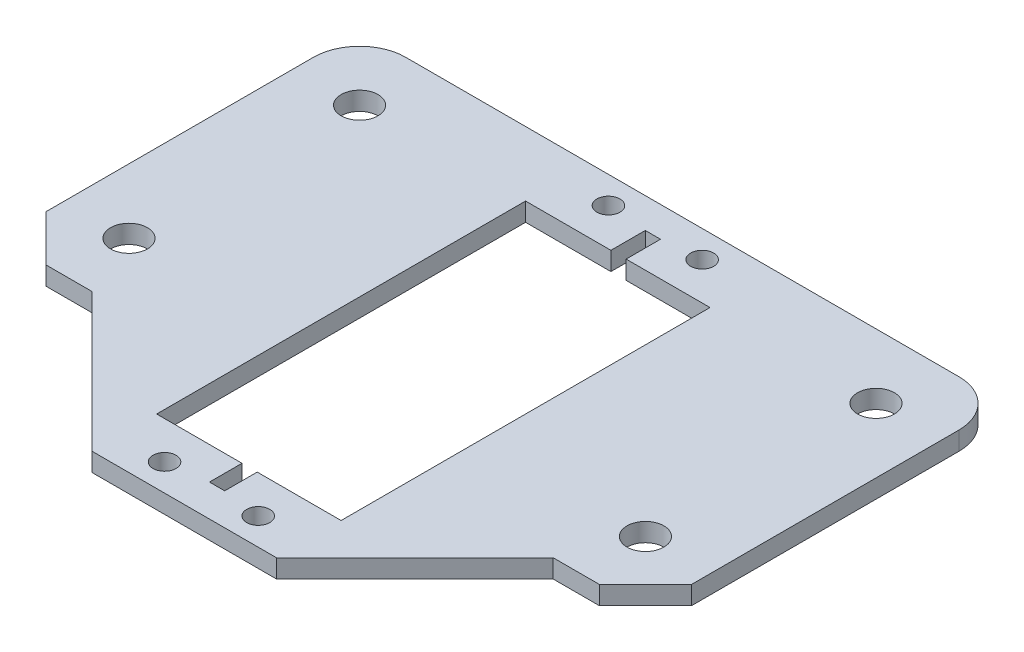
SolidWorks part; units mm, degrees
ref_plane "Спереди" through (0, 0, 0) normal (0, 0, 1) x (1, 0, 0)
ref_plane "Сверху" through (0, 0, 0) normal (0, 1, 0) x (1, 0, 0)
ref_plane "Справа" through (0, 0, 0) normal (1, 0, 0) x (0, 0, -1)
sketch "Эскиз1" plane through (0, 0, 0) normal (0, 1, 0) x (1, 0, 0)
  line L0 (-5.8393, -6.3286) -> (-5.8393, -60.3286) construction
  line L1 (-15.8393, -13.3286) -> (4.1607, -13.3286)
  line L2 (-15.8393, -13.3286) -> (-15.8393, -53.3286)
  line L3 (-15.8393, -53.3286) -> (4.1607, -53.3286)
  line L4 (4.1607, -13.3286) -> (4.1607, -53.3286)
  line L5 (-30.8393, -6.3286) -> (19.1607, -6.3286)
  line L6 (-30.8393, -6.3286) -> (-30.8393, -60.3286)
  line L7 (-30.8393, -60.3286) -> (19.1607, -60.3286)
  line L8 (19.1607, -6.3286) -> (19.1607, -60.3286)
  dimension "D1" = 40
  dimension "D2" = 20
  dimension "D3" = 10
  dimension "D4" = 7
  dimension "D5" = 7
  dimension "D6" = 15
extrude "Бобышка-Вытянуть1" add sketch "Эскиз1" along normal blind 2
sketch "Эскиз2" plane through (0, 2, 0) normal (0, 1, 0) x (1, 0, 0)
  circle A0 centre (-10.9193, -57.3951) radius 1.25
  circle A1 centre (-0.7593, -57.3951) radius 1.25
  circle A2 centre (-10.9193, -9.2621) radius 1.25
  circle A3 centre (-0.7593, -9.2621) radius 1.25
  dimension "D1" = 2.5
  dimension "D2" = 2.5
  dimension "D3" = 2.5
  dimension "D4" = 2.5
extrude "Вырез-Вытянуть1" cut sketch "Эскиз2" against normal blind 2
chamfer "Фаска1" distance 15 angle 45 2 edges at (19.1607, 1, 60.3286) (-30.8393, 1, 60.3286)
sketch "Эскиз3" plane through (19.1607, 0, 0) normal (1, 0, 0) x (0, 0, -1)
  line L1 (-45.3286, 2) -> (-6.3286, 2)
  line L2 (-45.3286, 2) -> (-45.3286, 0)
  line L3 (-45.3286, 0) -> (-6.3286, 0)
  line L4 (-6.3286, 2) -> (-6.3286, 0)
extrude "Бобышка-Вытянуть2" add sketch "Эскиз3" along normal blind 10
sketch "Эскиз4" plane through (-30.8393, 0, 0) normal (-1, 0, 0) x (0, 0, 1)
  line L1 (6.3286, 2) -> (45.3286, 2)
  line L2 (6.3286, 2) -> (6.3286, 0)
  line L3 (6.3286, 0) -> (45.3286, 0)
  line L4 (45.3286, 2) -> (45.3286, 0)
extrude "Бобышка-Вытянуть3" add sketch "Эскиз4" along normal blind 10
chamfer "Фаска2" distance 5 angle 45 2 edges at (29.1607, 1, 45.3286) (-40.8393, 1, 45.3286)
sketch "Эскиз5" plane through (0, 2, 0) normal (0, 1, 0) x (1, 0, 0)
  line L0 (-45.3622, -38.3286) -> (40.9463, -38.3286) construction
  line L1 (-5.8393, -6.3286) -> (-5.8393, -60.3286) construction
  line L2 (29.1607, -6.3286) -> (-40.8393, -6.3286) construction
  line L3 (-15.8393, -60.3286) -> (4.1607, -60.3286) construction
  line L4 (-33.8393, -38.3286) -> (-33.8393, -13.3286) construction
  line L5 (-33.8393, -13.3286) -> (22.1607, -13.3286) construction
  line L6 (22.1607, -13.3286) -> (22.1607, -38.3286) construction
  circle A0 centre (22.1607, -38.3286) radius 2
  circle A1 centre (-33.8393, -38.3286) radius 2
  circle A2 centre (-33.8393, -13.3286) radius 2
  circle A3 centre (22.1607, -13.3286) radius 2
  dimension "D1" = 56
  dimension "D3" = 4
  dimension "D4" = 4
  dimension "D6" = 4
  dimension "D7" = 4
  dimension "D2" = 28
  dimension "D5" = 22
  dimension "D8" = 25
extrude "Вырез-Вытянуть2" cut sketch "Эскиз5" against normal blind 10
sketch "Эскиз6" plane through (0, 0, 0) normal (0, -1, 0) x (1, 0, 0)
  line L0 (-6.5865, 53.3286) -> (-6.5865, 56.8559)
  line L1 (-15.8393, 53.3286) -> (4.1607, 53.3286) construction
  line L2 (-6.5865, 56.8559) -> (-4.9362, 56.8559)
  line L3 (-4.9362, 56.8559) -> (-4.9362, 53.3286)
  line L5 (-4.9362, 13.3286) -> (-4.9362, 9.6004)
  line L6 (4.1607, 13.3286) -> (-15.8393, 13.3286) construction
  line L7 (-4.9362, 9.6004) -> (-6.5865, 9.6004)
  line L8 (-6.5865, 9.6004) -> (-6.5865, 13.3286)
  line L9 (-6.5865, 13.3286) -> (-4.9362, 13.3286)
  line L10 (-4.9362, 53.3286) -> (-6.5865, 53.3286)
extrude "Вырез-Вытянуть3" cut sketch "Эскиз6" against normal blind 10
fillet "Скругление2" radius 5 2 edges at (-40.8393, 1, 6.3286) (29.1607, 1, 6.3286)
